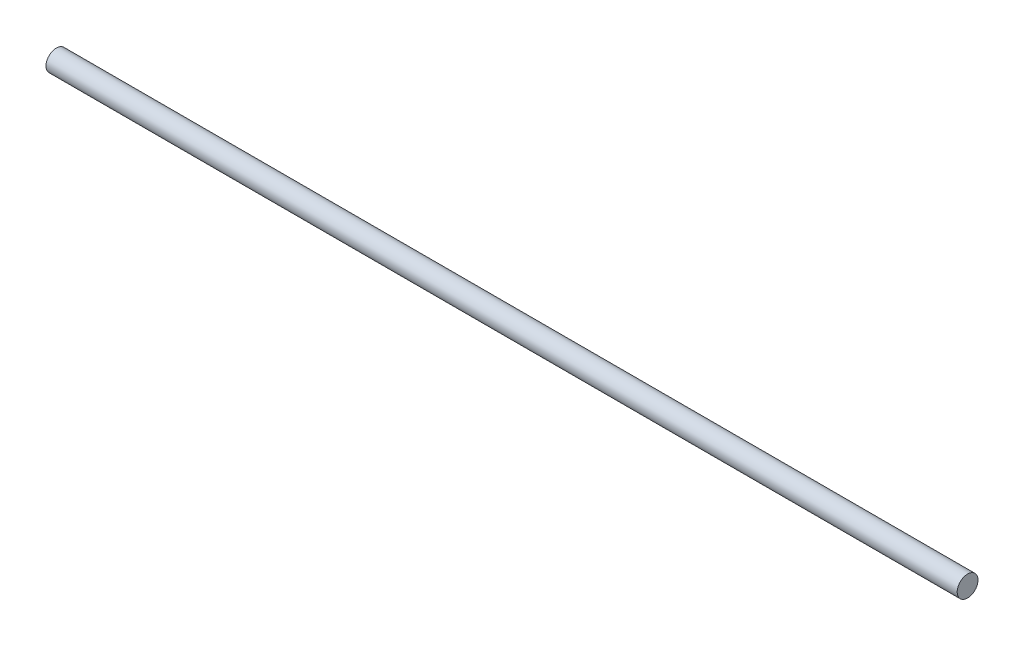
SolidWorks part; units mm, degrees
ref_plane "Front Plane" through (0, 0, 0) normal (0, 0, 1) x (1, 0, 0)
ref_plane "Top Plane" through (0, 0, 0) normal (0, 1, 0) x (1, 0, 0)
ref_plane "Right Plane" through (0, 0, 0) normal (1, 0, 0) x (0, 0, -1)
sketch "Sketch1" plane through (0, 0, 0) normal (0, 0, 1) x (1, 0, 0)
  line L0 (0, 4) -> (0, 0)
  line L1 (0, 0) -> (350, 0)
  line L2 (350, 0) -> (350, 4)
  line L3 (350, 4) -> (0, 4)
  line L4 (0, 0) -> (350, 0) construction
  dimension "D1" = 350
  dimension "D2" = 4
revolve "Revolve1" add sketch "Sketch1" angle 360 about L4
